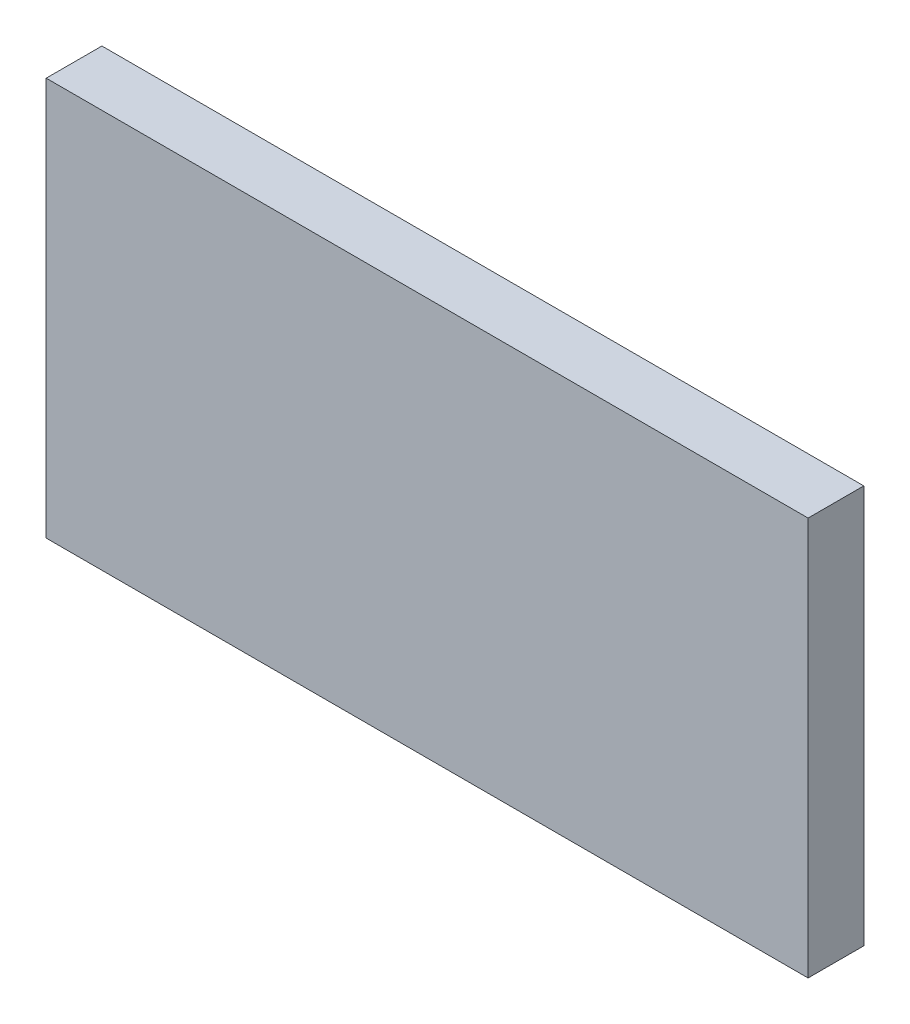
SolidWorks part; units mm, degrees
ref_plane "Front Plane" through (0, 0, 0) normal (0, 0, 1) x (1, 0, 0)
ref_plane "Top Plane" through (0, 0, 0) normal (0, 1, 0) x (1, 0, 0)
ref_plane "Right Plane" through (0, 0, 0) normal (1, 0, 0) x (0, 0, -1)
sketch "Sketch1" plane through (0, 0, 0) normal (0, 0, 1) x (1, 0, 0)
  line L1 (-66.9665, 38.5909) -> (69.8041, 38.5909)
  line L2 (-66.9665, 38.5909) -> (-66.9665, -32.9157)
  line L3 (-66.9665, -32.9157) -> (69.8041, -32.9157)
  line L4 (69.8041, 38.5909) -> (69.8041, -32.9157)
extrude "Boss-Extrude2" add sketch "Sketch1" along normal mid plane 10
